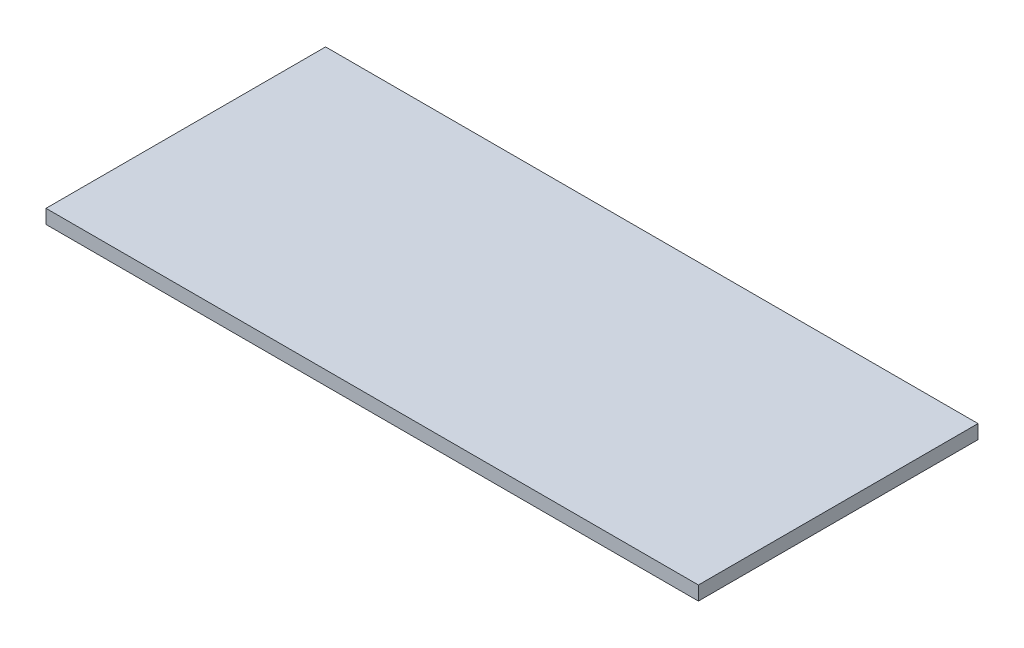
SolidWorks part; units mm, degrees
ref_plane "Plano frontal" through (0, 0, 0) normal (0, 0, 1) x (1, 0, 0)
ref_plane "Plano superior" through (0, 0, 0) normal (0, 1, 0) x (1, 0, 0)
ref_plane "Plano direito" through (0, 0, 0) normal (1, 0, 0) x (0, 0, -1)
sketch "Esboço1" plane through (0, 0, 0) normal (0, 1, 0) x (1, 0, 0)
  line L1 (350, -150) -> (-350, -150)
  line L2 (350, -150) -> (350, 150)
  line L3 (350, 150) -> (-350, 150)
  line L4 (-350, -150) -> (-350, 150)
  line L5 (350, -150) -> (-350, 150) construction
  line L6 (350, 150) -> (-350, -150) construction
  point P0 (0, 0)
  dimension "D1" = 300
  dimension "D2" = 700
extrude "Ressalto-extrusão1" add sketch "Esboço1" along normal blind 15
